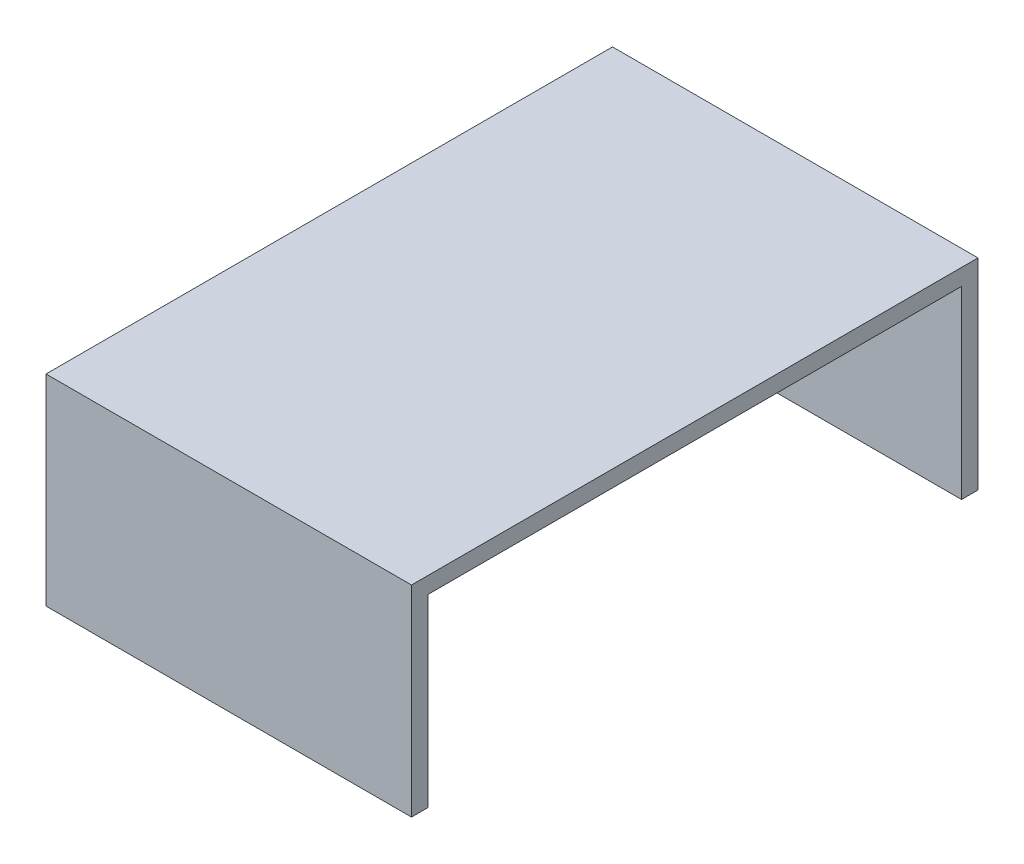
SolidWorks part; units mm, degrees
ref_plane "Alzado" through (0, 0, 0) normal (0, 0, 1) x (1, 0, 0)
ref_plane "Planta" through (0, 0, 0) normal (0, 1, 0) x (1, 0, 0)
ref_plane "Vista lateral" through (0, 0, 0) normal (1, 0, 0) x (0, 0, -1)
ref_plane "Plano4" through (10, 0, 0) normal (1, 0, 0) x (0, 0, -1)
sketch "Croquis1" plane through (10, 0, 0) normal (1, 0, 0) x (0, 0, -1)
  line L0 (7.75, 0) -> (-7.75, 0)
  line L1 (-7.75, 0) -> (-7.75, -5.5)
  line L2 (-7.75, -5.5) -> (-7.3, -5.5)
  line L3 (-7.3, -5.5) -> (-7.3, -0.45)
  line L4 (-7.3, -0.45) -> (7.3, -0.45)
  line L5 (7.3, -0.45) -> (7.3, -5.5)
  line L6 (7.3, -5.5) -> (7.75, -5.5)
  line L7 (7.75, -5.5) -> (7.75, 0)
extrude "Saliente-Extruir1" add sketch "Croquis1" against normal blind 10
